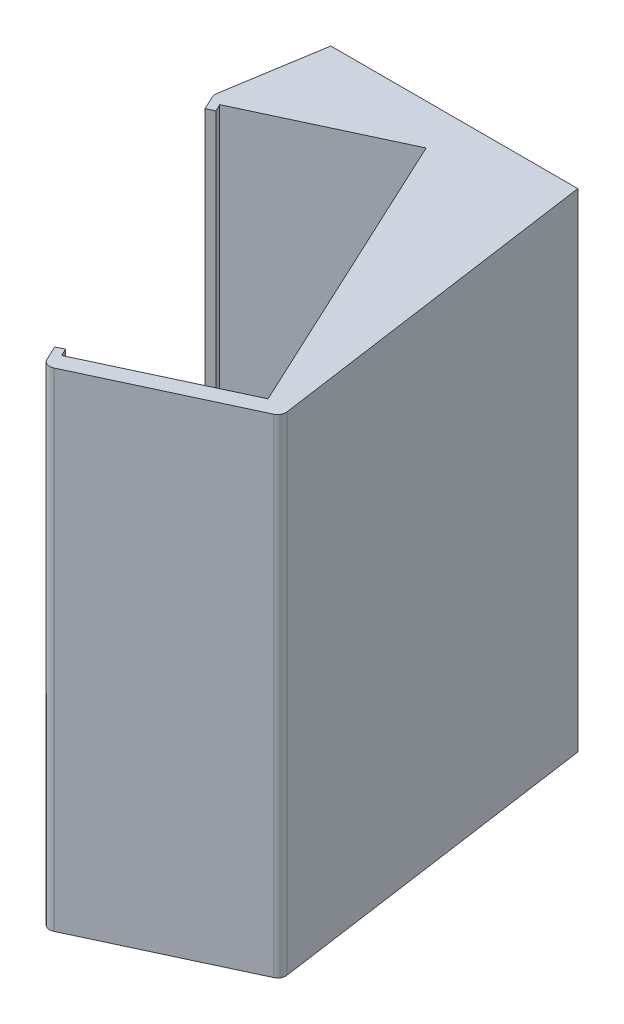
SolidWorks part; units mm, degrees
ref_plane "Front Plane" through (0, 0, 0) normal (1, 0, 0) x (0, 1, 0)
ref_plane "Top Plane" through (0, 0, 0) normal (0, 0, 1) x (0, 1, 0)
ref_plane "Right Plane" through (0, 0, 0) normal (0, 1, 0) x (-1, 0, 0)
sketch "Sketch1" plane through (0, 0, 0) normal (0, 1, 0) x (-1, 0, 0)
  line L0 (-5.1249, 10.9903) -> (3.4785, -7.4597) construction
  line L1 (0, 0) -> (-16.9893, 36.4336)
  line L2 (0, 0) -> (17.3105, 8.072)
  line L3 (-16.9893, 36.4336) -> (0.3212, 44.5056)
  line L4 (17.3105, 8.072) -> (0.3212, 44.5056)
  dimension "D1" = 19.1
  dimension "D2" = 40.2
sketch "Sketch2" plane through (0, 0, 0) normal (0, 1, 0) x (-1, 0, 0)
  line L0 (0.7438, 43.5993) -> (1.6502, 44.0219)
  line L1 (17.3105, 8.072) -> (0.3212, 44.5056) construction
  line L2 (1.6502, 44.0219) -> (0.3823, 46.7408)
  line L3 (0.3823, 46.7408) -> (-19.6471, 37.401)
  line L4 (-19.6471, 37.401) -> (-13.6471, -5)
  line L5 (-13.6471, -5) -> (16.7268, -5)
  line L7 (17.7942, 9.4009) -> (16.8879, 8.9783)
  line L8 (16.8879, 8.9783) -> (17.3105, 8.072)
  line L9 (17.3105, 8.072) -> (0, 0)
  line L10 (0, 0) -> (-16.9893, 36.4336)
  line L11 (-16.9893, 36.4336) -> (0.3212, 44.5056)
  line L12 (0.3212, 44.5056) -> (0.7438, 43.5993)
  line L13 (-84528.7772, 181272.5477) -> (84527.1309, -181269.0171) construction
  line L14 (17.7942, 9.4009) -> (18.7268, 7.4009)
  line L15 (18.7268, 7.4009) -> (16.7268, -5)
  dimension "D1" = 1
  dimension "D2" = 1
  dimension "D3" = 2
  dimension "D4" = 2
  dimension "D5" = 5
  dimension "D6" = 1
  dimension "D7" = 1
  dimension "D8" = 2
  dimension "D9" = 6
  dimension "D10" = 2
extrude "Boss-Extrude1" add sketch "Sketch2" along normal blind 60
fillet "Fillet1" radius 1 3 edges at (19.6471, 30, 37.401) (-18.7268, 30, 7.4009) (-0.3823, 30, 46.7408)
